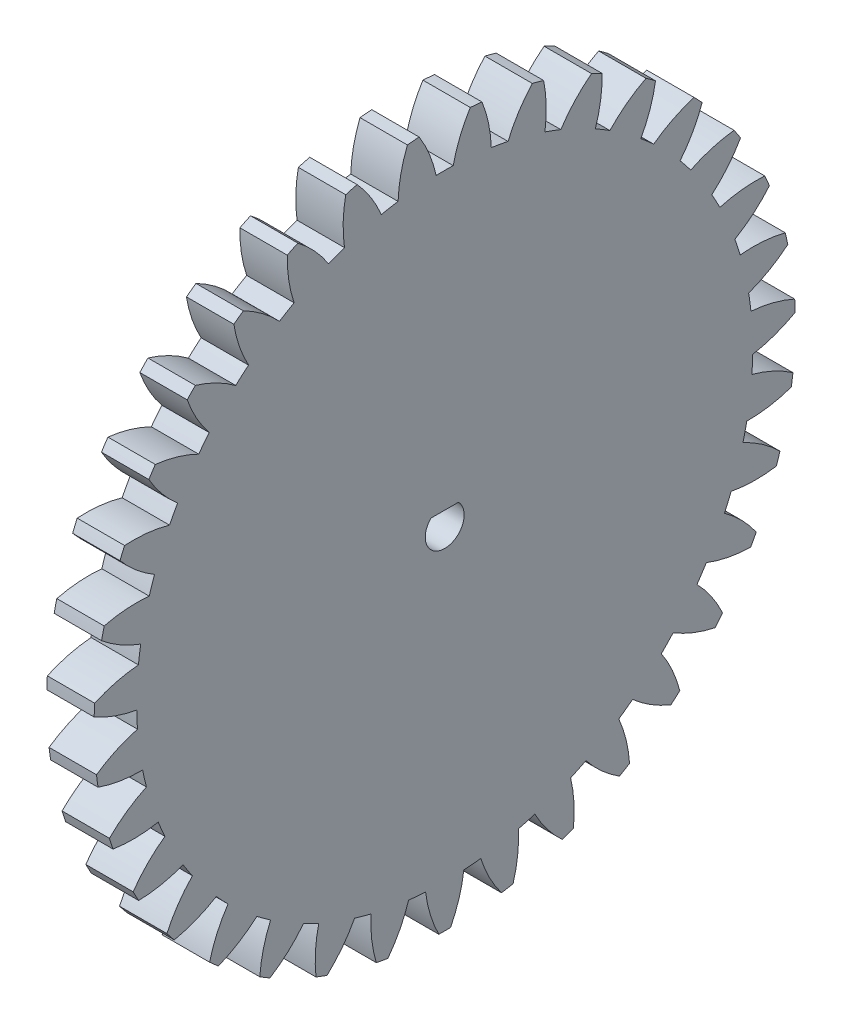
SolidWorks part; units mm, degrees
ref_plane "Plane1" through (0, 0, 0) normal (0, 0, 1) x (1, 0, 0)
ref_plane "Plane2" through (0, 0, 0) normal (0, 1, 0) x (1, 0, 0)
ref_plane "Plane3" through (0, 0, 0) normal (1, 0, 0) x (0, 0, -1)
sketch "HoldingSke" plane through (0, 0, 0) normal (0, 1, 0) x (1, 0, 0)
  line L0 (0, 0) -> (0.4096, -0.2868)
  line L1 (-15, 0) -> (100, 0) construction
  line L2 (0, 0) -> (-2.1039, 2.3779)
  line L3 (0, 0) -> (-11.863, 4.5341)
  line L4 (0, 0) -> (7.0742, 4.9534)
  line L5 (0, 0) -> (-46.8476, -17.4728)
  line L6 (0, 0) -> (-4.1448, -2.7965)
  line L7 (-2.1039, 2.3779) -> (8.6586, 51.2059)
  line L8 (-76.2, 54.61) -> (-75.9, 54.61)
  line L9 (-71.009, 38.7566) -> (-53.1078, 45.2721)
  line L10 (-76.2, 71.12) -> (104.1128, 71.12)
  line L11 (0, 0) -> (-5, 0)
  line L12 (-76.2, 101.6) -> (-76.133, 101.6)
  line L13 (24.9733, 27.94) -> (52.9518, 28.4284)
  line L14 (24.9733, 27.94) -> (24.9743, 27.94)
  line L15 (24.9733, 27.94) -> (100.4006, 29.5858)
  line L16 (-63.627, -2) -> (-12.827, -2)
  circle A0 centre (0, 0) radius 1
  circle A1 centre (0, 0) radius 32.499
  circle A2 centre (0, 0) radius 37.5
  circle A3 centre (0, 0) radius 1
  dimension "MHD" = 64.998
  dimension "Hub_dia" = 75
  dimension "Bore" = 2
  dimension "MBD" = 2
  dimension "Num_teeth" = 35
  dimension "Pitch" = 0.5
  dimension "Overall_len" = 50
  dimension "Show_teeth" = 35
  dimension "Thickness" = 5
  dimension "OAL" = 50.0001
  dimension "T_dim" = 0.3
  dimension "Ap" = 20
  dimension "H" = 19.05
  dimension "Pitch_radius" = 180.3128
  dimension "Width" = 5
  dimension "Backlash" = 0.067
  dimension "Addendum_fac" = 1
  dimension "Dedendum_fac" = 1.25
  dimension "Clearance_fac" = 0.25
  dimension "Dedendum_add" = 0.001
  dimension "Module" = 2
sketch "BasProSke" plane through (0, 0, 0) normal (0, 1, 0) x (1, 0, 0)
  line L0 (-10, 0) -> (60, 0) construction
  line L1 (0, 0) -> (0, 37)
  line L2 (0, 0) -> (5, 0)
  line L3 (5, 0) -> (5, 37)
  line L4 (5, 37) -> (0, 37)
  dimension "Thickness" = 5
  dimension "Diameter" = 74
revolve "Base-Revolve" add sketch "BasProSke" angle 360 about L0
sketch "TooCutSke" plane through (0, 0, 0) normal (1, 0, 0) x (0, 0, -1)
  line L1 (0, 0) -> (0, 107) construction
  line L2 (0, 0) -> (-1.6875, 34.9593) construction
  line L3 (0, 0) -> (-6.2693, 69.6581) construction
  line L4 (-1.6875, 34.9593) -> (-3.1347, 34.829) construction
  arc A0 (0.8983, 32.4866) -> (-0.8983, 32.4866) centre (0, 0) ccw
  arc A1 (2.714, 36.9258) -> (-2.714, 36.9258) centre (0, 0) ccw
  circle A2 centre (0, 0) radius 35 construction
  circle A3 centre (0, 0) radius 32.8892 construction
  arc A4 (-0.8983, 32.4866) -> (-2.714, 36.9258) centre (-14.5727, 29.4846) ccw
  arc A5 (2.714, 36.9258) -> (0.8983, 32.4866) centre (14.5727, 29.4846) ccw
  dimension "Root_dia" = 64.998
  dimension "Overcut_dia" = 74.0508
  dimension "Pitch_dia" = 70
  dimension "Base_dia" = 65.7785
  dimension "Flank_rad" = 14
  dimension "Half_ang" = 5.143
  dimension "Half_CT" = 1.453
extrude "ToothCut" cut sketch "TooCutSke" along normal through all
fillet "Breaks" [suppressed] radius 0.04
fillet "RootFillets" [suppressed] radius 0.501
pattern_circular "TeethCuts" count 35 every 10.286 about axis through (-10, 0, 0) along (1, 0, 0) of "ToothCut", "RootFillets", "Breaks"
sketch "HubNeaOneSke" plane through (0, 0, 0) normal (-1, 0, 0) x (0, 0, 1)
  circle A0 centre (0, 0) radius 32.499
  dimension "Diameter" = 64.998
extrude "HubNearOne" [suppressed] add sketch "HubNeaOneSke" along normal blind 45.0001
sketch "HubNeaBotSke" plane through (0, 0, 0) normal (-1, 0, 0) x (0, 0, 1)
  circle A0 centre (0, 0) radius 32.499
  dimension "Diameter" = 64.998
extrude "HubNearBoth" [suppressed] add sketch "HubNeaBotSke" along normal blind 22.5
ref_plane "FarPln" through (5, 0, 0) normal (1, 0, 0) x (0, 0, -1)
sketch "HubFarSke" plane through (5, 0, 0) normal (1, 0, 0) x (0, 0, -1)
  circle A0 centre (0, 0) radius 32.499
  dimension "Diameter" = 64.998
extrude "HubFar" [suppressed] add sketch "HubFarSke" along normal blind 22.5
sketch "BorSke" plane through (0, 0, 0) normal (1, 0, 0) x (0, 0, -1)
  circle A0 centre (0, 0) radius 1
  dimension "Diameter" = 2
extrude "Bore" cut sketch "BorSke" along normal mid plane 100.0001
sketch "KeySke" plane through (0, 0, 0) normal (1, 0, 0) x (0, 0, -1)
  line L0 (-0.4, 0) -> (-0.4, 1.3)
  line L1 (-0.4, 1.3) -> (0.4, 1.3)
  line L2 (0.4, 1.3) -> (0.4, 0)
  line L3 (0, 0) -> (0, 34) construction
  line L4 (-0.4, 0) -> (0.4, 0)
  dimension "Offset" = 1.3
  dimension "Width" = 0.8
extrude "Keyway" [suppressed] cut sketch "KeySke" along normal mid plane 100.0001
pattern_circular "Keyway2" [suppressed] count 2 every 90 about axis through (-10, 0, 0) along (1, 0, 0)
ref_plane "Plane4" through (5, 0, 0) normal (1, 0, 0) x (0, 0, -1)
sketch "Sketch1" plane through (5, 0, 0) normal (1, 0, 0) x (0, 0, -1)
  line L0 (-1.4491, 1.45) -> (1.4491, 1.45)
  arc A0 (-1.4491, 1.45) -> (1.4491, 1.45) centre (0, 0) ccw
  dimension "D1" = 4.1
  dimension "D2" = 1.45
extrude "Cut-Extrude1" cut sketch "Sketch1" against normal blind 10
equation "' \"Module@HoldingSke\" = 6.35"
equation "' \"Num_teeth@HoldingSke\" = 12"
equation "' \"Ap@HoldingSke\" =  20"
equation "' \"Ap@HoldingSke\" = 20"
equation "' \"Width@HoldingSke\" = 0.5 * 25.4"
equation "' \"Hub_dia@HoldingSke\"= 1 * 25.4"
equation "' \"Hub_dia@HoldingSke\" = 1 * 25.4"
equation "' \"Overall_len@HoldingSke\" = 1.0 * 25.4"
equation "' \"Bore@HoldingSke\" = 0.75 * 25.4"
equation "' \"T_dim@HoldingSke\" = 0.1 * 25.4"
equation "' \"Width@KeySke\" = 0.25 * 25.4"
equation "' \"Show_teeth@HoldingSke\" = 13"
equation "' \"Backlash@HoldingSke\" = 0.009 * 25.4"
equation "' \"Addendum_fac@HoldingSke\" = 1.0"
equation "' \"Dedendum_fac@HoldingSke\" = 1.25"
equation "' \"Dedendum_add@HoldingSke\" = 0.00005 * 25.4"
equation "' \"Clearance_fac@HoldingSke\" = 0.25"
equation "\"Pitch@HoldingSke\" = 1 / \"Module@HoldingSke\""
equation "\"Overcut_dia@TooCutSke\" = (\"Num_teeth@HoldingSke\" + 2 * \"Addendum_fac@HoldingSke\") / \"Pitch@HoldingSke\" + 0.002 * 25.4"
equation "\"Pitch_dia@TooCutSke\" = \"Num_teeth@HoldingSke\" / \"Pitch@HoldingSke\""
equation "\"Base_dia@TooCutSke\" = \"Num_teeth@HoldingSke\" / \"Pitch@HoldingSke\" * cos((\"Ap@HoldingSke\"  * 3.14159265 / 180))"
equation "\"Root_dia@TooCutSke\" = (\"Num_teeth@HoldingSke\" + 2) / \"Pitch@HoldingSke\" - 2 * (\"Addendum_fac@HoldingSke\" + \"Dedendum_fac@HoldingSke\") / \"Pitch@HoldingSke\" - \"Dedendum_add@HoldingSke\" * 2"
equation "\"Half_ang@TooCutSke\" = 180 / \"Num_teeth@HoldingSke\""
equation "\"Half_CT@TooCutSke\" = \"Num_teeth@HoldingSke\" / \"Pitch@HoldingSke\" * sin((3.14159265 / 2 / \"Num_teeth@HoldingSke\")) / 2 - 7 * \"Backlash@HoldingSke\" / 4"
equation "\"Flank_rad@TooCutSke\" = \"Num_teeth@HoldingSke\" / \"Pitch@HoldingSke\" / 5"
equation "\"Radius@RootFillets\" = \"Clearance_fac@HoldingSke\" / \"Pitch@HoldingSke\" + \"Dedendum_add@HoldingSke\""
equation "\"Break_rad@Breaks\" = 0.02 / \"Pitch@HoldingSke\""
equation "\"Thickness@HoldingSke\" = \"Width@HoldingSke\""
equation "\"OAL@HoldingSke\" = \"Thickness@HoldingSke\""
equation "\"MHD@HoldingSke\" = (\"Num_teeth@HoldingSke\" + 2) / \"Pitch@HoldingSke\" - 2 * (\"Addendum_fac@HoldingSke\" + \"Dedendum_fac@HoldingSke\")  / \"Pitch@HoldingSke\" - \"Dedendum_add@HoldingSke\" * 2"
equation "\"MBD@HoldingSke\" = (\"Num_teeth@HoldingSke\" + 2) / \"Pitch@HoldingSke\" - 2 * (\"Addendum_fac@HoldingSke\" + \"Dedendum_fac@HoldingSke\")  / \"Pitch@HoldingSke\" - \"Dedendum_add@HoldingSke\" * 2 - 0.002 * 25.4"
equation "\"MHD@HoldingSke\" = ((sgn( \"MHD@HoldingSke\" - \"Hub_dia@HoldingSke\" )-1)*( \"MHD@HoldingSke\" - \"Hub_dia@HoldingSke\" ))/-2+ \"Hub_dia@HoldingSke\""
equation "\"MBD@HoldingSke\" = ((sgn( \"MBD@HoldingSke\" - \"Bore@HoldingSke\" )-1)*( \"MBD@HoldingSke\" - \"Bore@HoldingSke\" ))/-2+ \"Bore@HoldingSke\""
equation "\"OAL@HoldingSke\" = ((sgn( \"OAL@HoldingSke\" - \"Overall_len@HoldingSke\" )+1)*( \"OAL@HoldingSke\" - \"Overall_len@HoldingSke\" ))/2 + \"Overall_len@HoldingSke\" + 0.000002 * 25.4"
equation "\"Num_teeth@TeethCuts\" = int( \"Show_teeth@HoldingSke\" ) + 1"
equation "\"Num_teeth@TeethCuts\" = ((sgn( \"Num_teeth@TeethCuts\" - \"Num_teeth@HoldingSke\" )-1)*( \"Num_teeth@TeethCuts\" - \"Num_teeth@HoldingSke\" ))/-2+ \"Num_teeth@HoldingSke\""
equation "\"Num_teeth@TeethCuts\" = ((sgn( \"Num_teeth@TeethCuts\" - 2.0)+1)*( \"Num_teeth@TeethCuts\" - 2.0))/2 +2.0"
equation "\"Angle@TeethCuts\" = 360.0 / \"Num_teeth@HoldingSke\""
equation "\"Diameter@BasProSke\" = (\"Num_teeth@HoldingSke\" + 2 * \"Addendum_fac@HoldingSke\") / \"Pitch@HoldingSke\""
equation "\"Thickness@BasProSke\"  = \"Thickness@HoldingSke\""
equation "' \"Fillet_rad@BasProSke\" =  \"Thickness@HoldingSke\" * 0.05"
equation "' \"Fillet_rad@BasProSke\" = \"Thickness@HoldingSke\" * 0.05"
equation "\"MHD@HoldingSke\" = ((sgn( \"MHD@HoldingSke\" - \"Root_dia@TooCutSke\" )-1)*( \"MHD@HoldingSke\" - \"Root_dia@TooCutSke\" ))/-2+ \"Root_dia@TooCutSke\""
equation "\"Diameter@HubNeaOneSke\" = \"MHD@HoldingSke\""
equation "\"Length@HubNearOne\" = \"OAL@HoldingSke\" - \"Thickness@BasProSke\""
equation "\"Diameter@HubNeaBotSke\" = \"MHD@HoldingSke\""
equation "\"Length@HubNearBoth\" = ( \"OAL@HoldingSke\" - \"Thickness@BasProSke\" ) / 2.0"
equation "\"Thickness@FarPln\" = \"Thickness@BasProSke\""
equation "\"Diameter@HubFarSke\" = \"MHD@HoldingSke\""
equation "\"Length@HubFar\" = ( \"OAL@HoldingSke\" - \"Thickness@BasProSke\" ) / 2.0"
equation "\"Diameter@BorSke\" = \"MBD@HoldingSke\""
equation "\"D1@Bore\" = \"OAL@HoldingSke\" * 2.0"
equation "\"D1@Keyway\" = \"OAL@HoldingSke\" * 2.0"
equation "\"Offset@KeySke\" = \"T_dim@HoldingSke\" + \"MBD@HoldingSke\" / 2.0"
